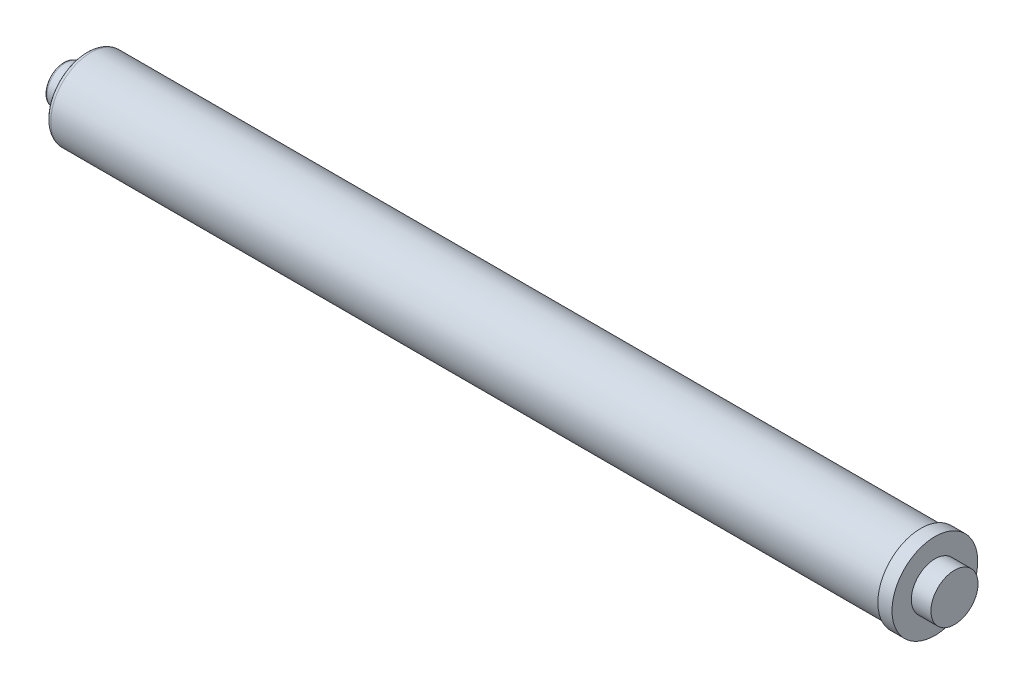
SolidWorks part; units mm, degrees
material "1060 Alloy"
ref_plane "Front Plane" through (0, 0, 0) normal (0, 0, 1) x (1, 0, 0)
ref_plane "Top Plane" through (0, 0, 0) normal (0, 1, 0) x (1, 0, 0)
ref_plane "Right Plane" through (0, 0, 0) normal (1, 0, 0) x (0, 0, -1)
sketch "Sketch1" plane through (0, 0, 0) normal (0, 1, 0) x (1, 0, 0)
  line L0 (-319.5622, 0) -> (364.5245, 0)
  line L1 (281.178, -26.9875) -> (-278.003, -26.9875)
  line L2 (281.178, -26.9875) -> (281.178, 26.9875)
  line L3 (281.178, 26.9875) -> (-278.003, 26.9875)
  line L4 (-281.178, -23.8125) -> (-281.178, 23.8125)
  line L5 (281.178, -26.9875) -> (-281.178, 26.9875) construction
  line L6 (281.178, 26.9875) -> (-281.178, -26.9875) construction
  line L8 (290.703, -28.8925) -> (281.178, -28.8925)
  line L9 (290.703, -28.8925) -> (290.703, 28.8925)
  line L10 (290.703, 28.8925) -> (281.178, 28.8925)
  line L11 (281.178, -28.8925) -> (281.178, 28.8925)
  line L12 (290.703, -28.8925) -> (281.178, 28.8925) construction
  line L13 (290.703, 28.8925) -> (281.178, -28.8925) construction
  line L14 (303.911, -15.875) -> (290.703, -15.875)
  line L15 (303.911, -15.875) -> (303.911, 15.875)
  line L16 (303.911, 15.875) -> (290.703, 15.875)
  line L17 (290.703, -15.875) -> (290.703, 15.875)
  line L18 (303.911, -15.875) -> (290.703, 15.875) construction
  line L19 (303.911, 15.875) -> (290.703, -15.875) construction
  line L20 (-294.8305, -12.7) -> (-281.178, -12.7)
  line L21 (-296.418, -11.1125) -> (-296.418, 11.1125)
  line L22 (-294.8305, 12.7) -> (-281.178, 12.7)
  line L23 (-281.178, -12.7) -> (-281.178, 12.7)
  line L24 (-296.418, -12.7) -> (-281.178, 12.7) construction
  line L25 (-296.418, 12.7) -> (-281.178, -12.7) construction
  arc A0 (-278.003, -26.9875) -> (-281.178, -23.8125) centre (-278.003, -23.8125) cw
  arc A1 (-278.003, 26.9875) -> (-281.178, 23.8125) centre (-278.003, 23.8125) ccw
  arc A2 (-294.8305, -12.7) -> (-296.418, -11.1125) centre (-294.8305, -11.1125) cw
  arc A3 (-296.418, 11.1125) -> (-294.8305, 12.7) centre (-294.8305, 11.1125) cw
  point P0 (0, 0)
  point P8 (285.9405, 0)
  point P13 (297.307, 0)
  point P18 (-288.798, 0)
  dimension "D9" = 3.175
  dimension "D10" = 1.5875
  dimension "D1" = 562.356
  dimension "D2" = 9.525
  dimension "D3" = 53.975
  dimension "D4" = 57.785
  dimension "D5" = 31.75
  dimension "D6" = 13.208
  dimension "D7" = 15.24
  dimension "D8" = 25.4
revolve "Revolve1" add sketch "Sketch1" angle 360 about L0
